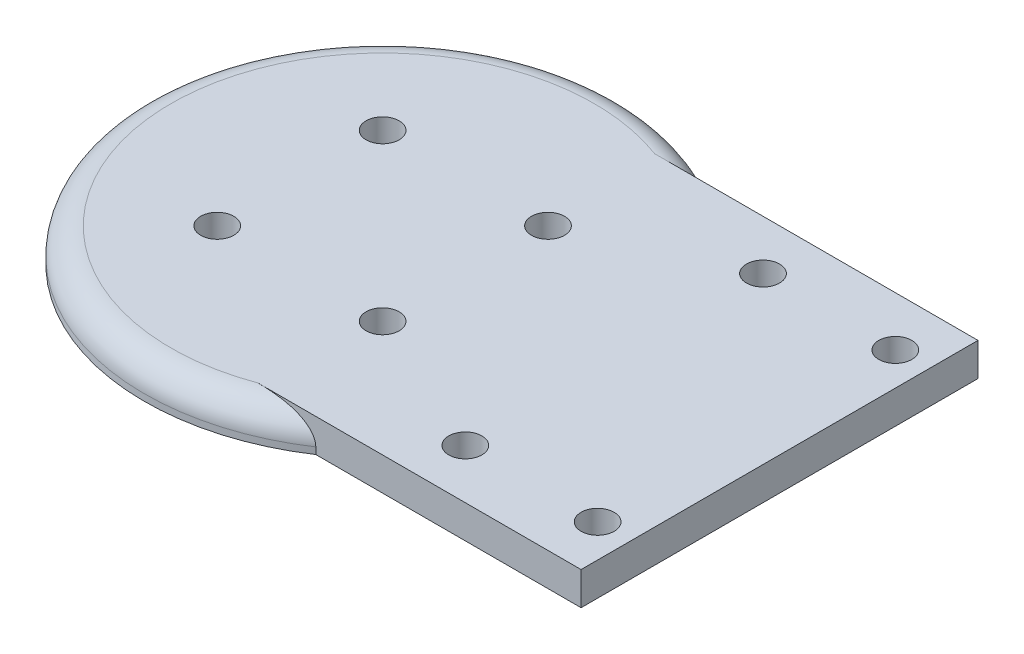
SolidWorks part; units mm, degrees
ref_plane "前视基准面" through (0, 0, 0) normal (0, 0, 1) x (1, 0, 0)
ref_plane "上视基准面" through (0, 0, 0) normal (0, 1, 0) x (1, 0, 0)
ref_plane "右视基准面" through (0, 0, 0) normal (1, 0, 0) x (0, 0, -1)
sketch "草图1" plane through (0, 0, 0) normal (0, 1, 0) x (1, 0, 0)
  line L1 (19.8997, -30) -> (60, -30)
  line L2 (60, -30) -> (60, 30)
  line L3 (60, 30) -> (19.8997, 30)
  arc A0 (19.8997, 30) -> (19.8997, -30) centre (0, 0) ccw
extrude "凸台-拉伸1" add sketch "草图1" along normal blind 5
fillet "圆角1" radius 4 1 edges at (-36, 5, 0)
sketch "草图2" plane through (0, 5, 0) normal (0, 1, 0) x (1, 0, 0)
  line L0 (10, 12.5) -> (12.5, 12.5)
  line L1 (-12.5, 12.5) -> (-10, 12.5)
  line L2 (-12.5, 12.5) -> (-12.5, 10)
  line L3 (-12.5, -12.5) -> (-10, -12.5)
  line L4 (12.5, 12.5) -> (12.5, 10)
  line L5 (-12.5, 12.5) -> (-10.7322, 10.7322) construction
  line L6 (-12.5, -12.5) -> (-10.7322, -10.7322) construction
  line L7 (10.7322, -10.7322) -> (12.5, -12.5) construction
  line L8 (-12.5, -10) -> (-12.5, -12.5)
  line L9 (10.7322, 10.7322) -> (12.5, 12.5) construction
  line L10 (12.5, -10) -> (12.5, -12.5)
  line L11 (10, -12.5) -> (12.5, -12.5)
  line L12 (0, 0) -> (45, 0)
  line L14 (35, 22.5) -> (55, 22.5)
  line L15 (35, 22.5) -> (35, -22.5)
  line L16 (35, -22.5) -> (55, -22.5)
  line L17 (55, 22.5) -> (55, -22.5)
  line L18 (35, 22.5) -> (55, -22.5) construction
  line L19 (35, -22.5) -> (55, 22.5) construction
  circle A0 centre (-12.5, 12.5) radius 2.5
  circle A1 centre (12.5, 12.5) radius 2.5
  circle A2 centre (12.5, -12.5) radius 2.5
  circle A3 centre (-12.5, -12.5) radius 2.5
  circle A4 centre (35, 22.5) radius 2.5
  circle A5 centre (55, 22.5) radius 2.5
  circle A6 centre (55, -22.5) radius 2.5
  circle A7 centre (35, -22.5) radius 2.5
  point P0 (0, 0)
  point P16 (0, 0)
  dimension "D1" = 4
  dimension "D5" = 2
  dimension "D2" = 45
  dimension "D3" = 45
  dimension "D4" = 20
  dimension "D6" = 2
extrude "切除-拉伸1" cut sketch "草图2" against normal through all contours A0 | A3 | A1 | A2 | A4 | A7 | A6 | A5
